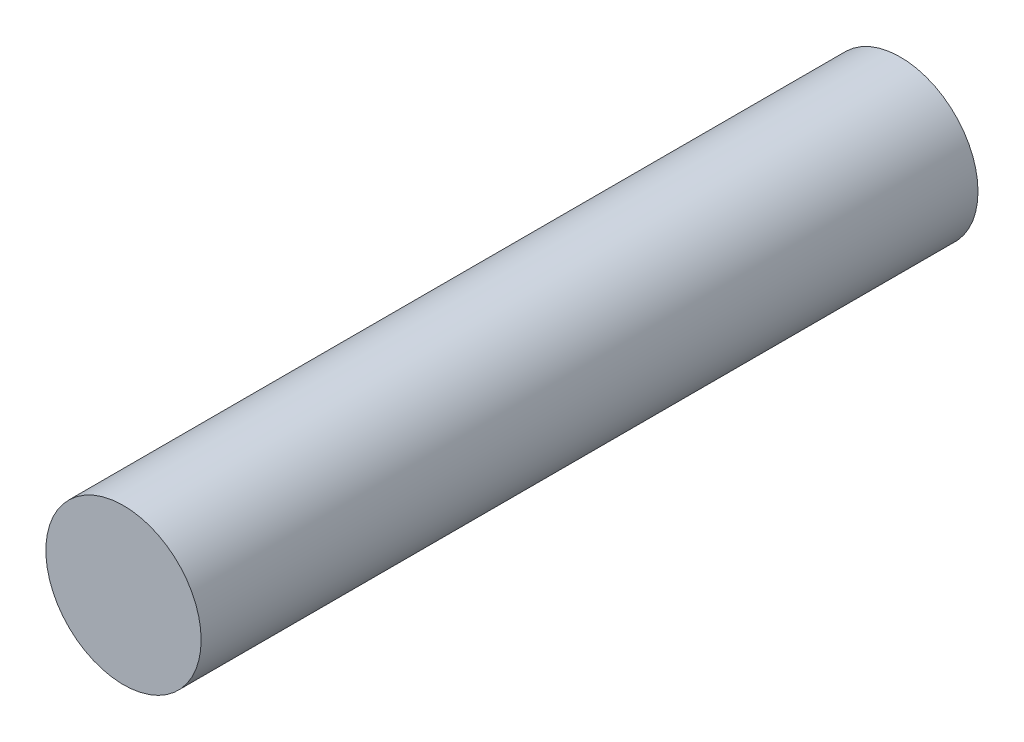
SolidWorks part; units mm, degrees
ref_plane "Front Plane" through (0, 0, 0) normal (0, 0, 1) x (1, 0, 0)
ref_plane "Top Plane" through (0, 0, 0) normal (0, 1, 0) x (1, 0, 0)
ref_plane "Right Plane" through (0, 0, 0) normal (1, 0, 0) x (0, 0, -1)
sketch "Sketch1" plane through (0, 0, 0) normal (0, 0, 1) x (1, 0, 0)
  circle A0 centre (0, 0) radius 4.9975
  dimension "D1" = 9.995
extrude "Boss-Extrude1" add sketch "Sketch1" along normal blind 6 and the other way blind 44
